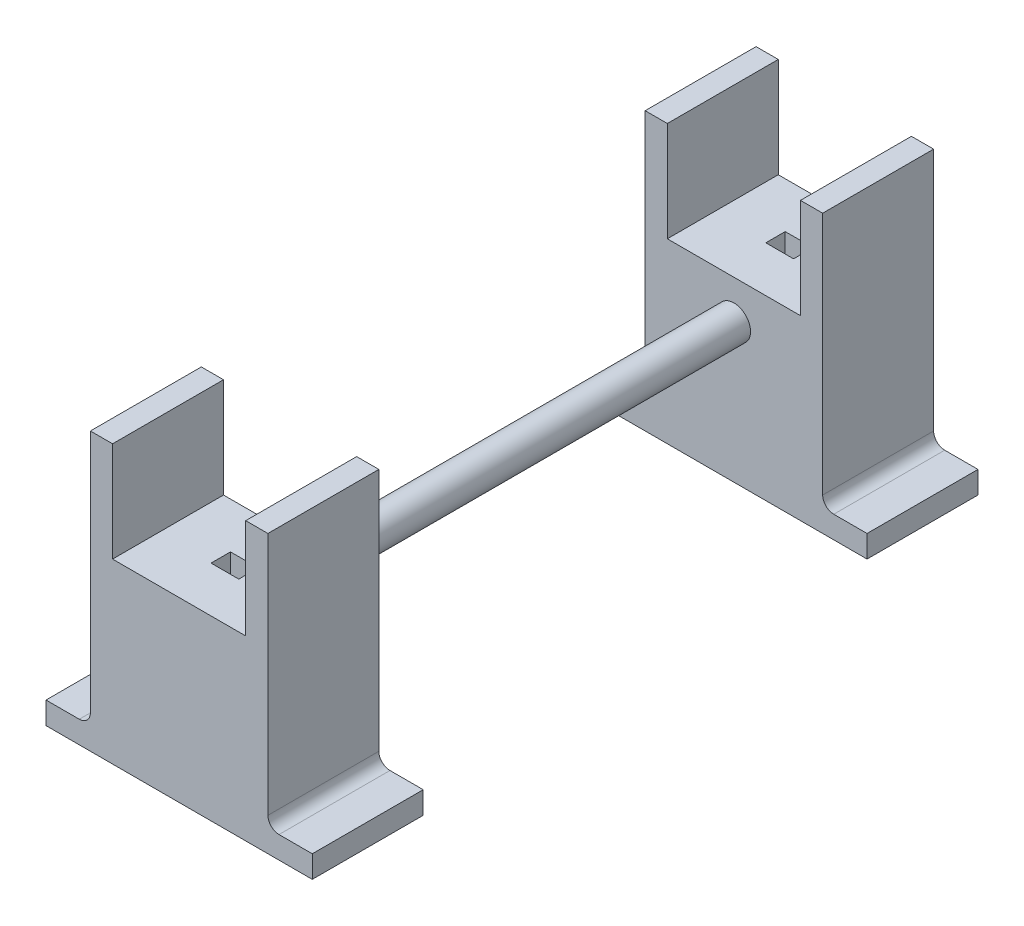
SolidWorks part; units mm, degrees
ref_plane "Front Plane" through (0, 0, 0) normal (0, 0, 1) x (1, 0, 0)
ref_plane "Top Plane" through (0, 0, 0) normal (0, 1, 0) x (1, 0, 0)
ref_plane "Right Plane" through (0, 0, 0) normal (1, 0, 0) x (0, 0, -1)
sketch "Sketch1" plane through (0, 0, 0) normal (0, 0, 1) x (1, 0, 0)
  circle A0 centre (0, 0) radius 3
  dimension "D1" = 6
extrude "Boss-Extrude1" add sketch "Sketch1" along normal mid plane 80
sketch "Sketch2" plane through (0, 0, 40) normal (0, 0, 1) x (1, 0, 0)
  line L8 (16, -25) -> (-16, -25)
  line L9 (16, -25) -> (16, 25)
  line L10 (16, 25) -> (-16, 25)
  line L11 (-16, -25) -> (-16, 25)
  line L12 (16, -25) -> (-16, 25) construction
  line L13 (16, 25) -> (-16, -25) construction
  point P0 (0, 0)
  dimension "D2" = 32
  dimension "D1" = 50
extrude "Boss-Extrude2" add sketch "Sketch2" along normal blind 20
sketch "Sketch9" plane through (0, -25, 0) normal (0, -1, 0) x (1, 0, 0)
  line L0 (-16, 60) -> (16, 60) construction
  line L1 (24, 40) -> (-24, 40)
  line L2 (24, 40) -> (24, 60)
  line L3 (24, 60) -> (-24, 60)
  line L4 (-24, 40) -> (-24, 60)
  line L5 (24, 40) -> (-24, 60) construction
  line L6 (24, 60) -> (-24, 40) construction
  line L7 (-3, 40) -> (3, 40) construction
  line L8 (16, 60) -> (16, 40) construction
  line L9 (-16, 60) -> (-16, 40) construction
  point P0 (0, 50)
  dimension "D1" = 8
  dimension "D2" = 8
extrude "Boss-Extrude5" add sketch "Sketch9" against normal blind 4
fillet "Fillet1" radius 2 2 edges at (-16, -21, 50) (16, -21, 50)
sketch "Sketch10" plane through (0, 25, 0) normal (0, 1, 0) x (1, 0, 0)
  line L5 (-12, -40) -> (12, -40)
  line L6 (-12, -40) -> (-12, -60)
  line L7 (-12, -60) -> (12, -60)
  line L8 (16, -40) -> (-16, -40)
  line L9 (-16, -40) -> (-16, -60)
  line L10 (-16, -60) -> (16, -60)
  line L11 (16, -60) -> (16, -40)
  line L12 (16, -40) -> (-16, -40) construction
  line L13 (-16, -40) -> (-16, -60) construction
  line L14 (-16, -60) -> (16, -60) construction
  line L15 (16, -60) -> (16, -40) construction
  line L16 (12, -40) -> (12, -60)
  dimension "D2" = 4
  dimension "D3" = 4
  dimension "D1" = 0
extrude "Cut-Extrude2" cut sketch "Sketch10" against normal blind 18
sketch "Sketch11" plane through (0, 7, 0) normal (0, 1, 0) x (1, 0, 0)
  line L0 (12, -40) -> (-12, -40) construction
  line L1 (-2.5, -51.75) -> (2.5, -51.75)
  line L2 (-2.5, -51.75) -> (-2.5, -48.25)
  line L3 (-2.5, -48.25) -> (2.5, -48.25)
  line L4 (2.5, -51.75) -> (2.5, -48.25)
  line L5 (-2.5, -51.75) -> (2.5, -48.25) construction
  line L6 (-2.5, -48.25) -> (2.5, -51.75) construction
  line L7 (12, -60) -> (12, -40) construction
  point P0 (0, -50)
  point P5 (0, -48.25)
  point P8 (0, -40)
  point P11 (12, -50)
  point P12 (2.5, -50)
  dimension "D1" = 3.5
  dimension "D2" = 5
extrude "Cut-Extrude3" cut sketch "Sketch11" against normal blind 5
mirror "Mirror5" about plane through (0, 0, 0) normal (0, 0, 1) of "Cut-Extrude3", "Cut-Extrude2", "Boss-Extrude2", "Boss-Extrude5", "Fillet1"
